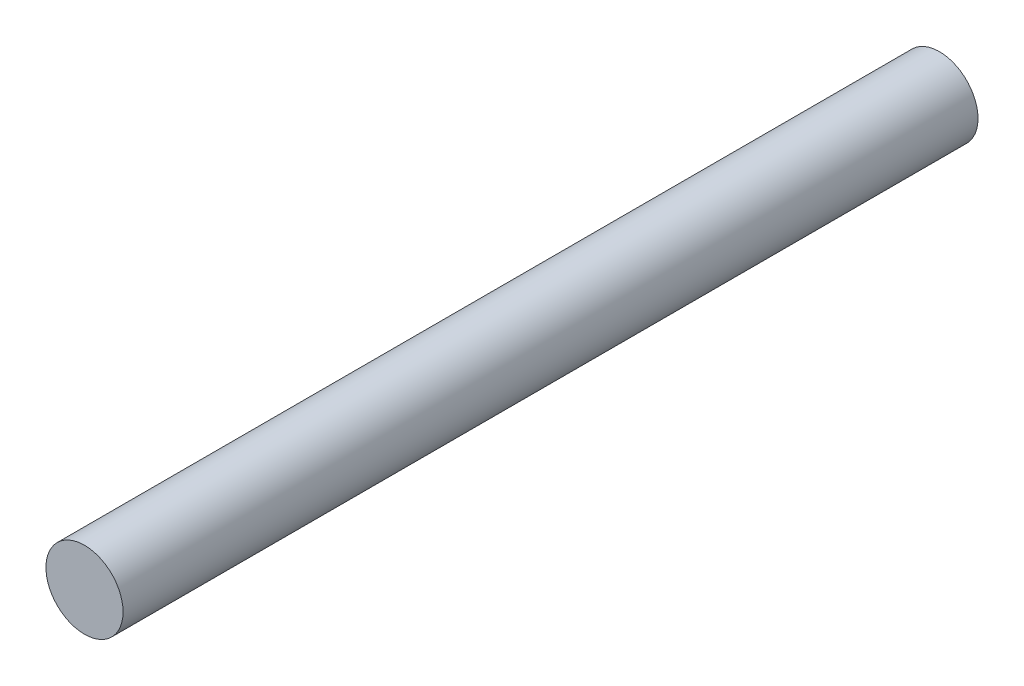
SolidWorks part; units mm, degrees
ref_plane "Front Plane" through (0, 0, 0) normal (0, 0, 1) x (1, 0, 0)
ref_plane "Top Plane" through (0, 0, 0) normal (0, 1, 0) x (1, 0, 0)
ref_plane "Right Plane" through (0, 0, 0) normal (1, 0, 0) x (0, 0, -1)
sketch "Sketch1" plane through (0, 0, 0) normal (0, 0, 1) x (1, 0, 0)
  circle A0 centre (0, 0) radius 0.3
  dimension "D1" = 0.6
extrude "Boss-Extrude1" add sketch "Sketch1" along normal blind 6.65
